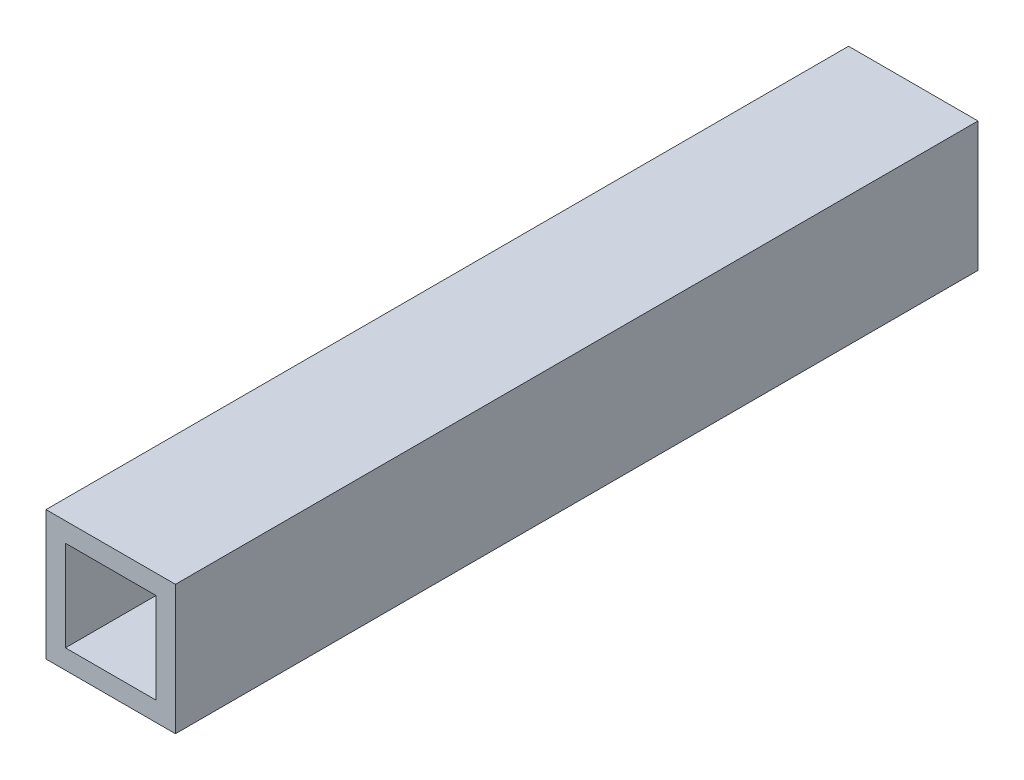
SolidWorks part; units mm, degrees
ref_plane "Front Plane" through (0, 0, 0) normal (0, 0, 1) x (1, 0, 0)
ref_plane "Top Plane" through (0, 0, 0) normal (0, 1, 0) x (1, 0, 0)
ref_plane "Right Plane" through (0, 0, 0) normal (1, 0, 0) x (0, 0, -1)
sketch "Sketch1" plane through (0, 0, 0) normal (0, 0, 1) x (1, 0, 0)
  line L1 (-5, 5) -> (5, 5)
  line L2 (-5, 5) -> (-5, -5)
  line L3 (-5, -5) -> (5, -5)
  line L4 (5, 5) -> (5, -5)
  line L5 (-5, 5) -> (5, -5) construction
  line L6 (-5, -5) -> (5, 5) construction
  line L7 (-3.5, -3.5) -> (3.5, -3.5)
  line L8 (-3.5, -3.5) -> (-3.5, 3.5)
  line L9 (-3.5, 3.5) -> (3.5, 3.5)
  line L10 (3.5, -3.5) -> (3.5, 3.5)
  line L11 (-3.5, -3.5) -> (3.5, 3.5) construction
  line L12 (-3.5, 3.5) -> (3.5, -3.5) construction
  point P0 (0, 0)
  point P6 (0, 0)
  dimension "D1" = 10
  dimension "D2" = 10
  dimension "D3" = 1.5
extrude "Boss-Extrude1" add sketch "Sketch1" along normal blind 62
